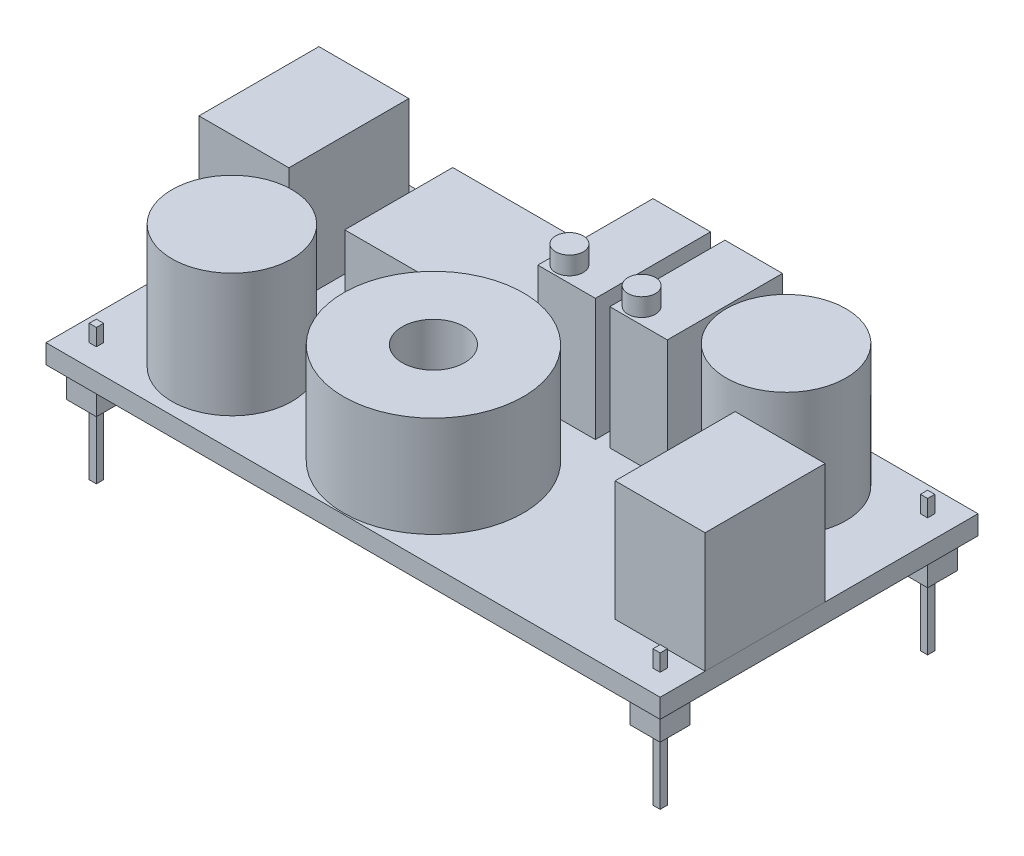
SolidWorks part; units mm, degrees
ref_plane "Plan de face" through (0, 0, 0) normal (0, 0, 1) x (1, 0, 0)
ref_plane "Plan de dessus" through (0, 0, 0) normal (0, 1, 0) x (1, 0, 0)
ref_plane "Plan de droite" through (0, 0, 0) normal (1, 0, 0) x (0, 0, -1)
sketch "Esquisse1" plane through (0, 0, 0) normal (0, 1, 0) x (1, 0, 0)
  line L1 (-25.6, 13.25) -> (25.6, 13.25)
  line L2 (-25.6, 13.25) -> (-25.6, -13.25)
  line L3 (-25.6, -13.25) -> (25.6, -13.25)
  line L4 (25.6, 13.25) -> (25.6, -13.25)
  point P4 (0, 13.25)
  point P6 (-25.6, 0)
  dimension "D1" = 51.2
  dimension "D2" = 26.5
extrude "Boss.-Extru.1" add sketch "Esquisse1" along normal blind 1.6
sketch "Esquisse2" plane through (0, 1.6, 0) normal (0, 1, 0) x (1, 0, 0)
  line L0 (-25.6, 13.25) -> (-25.6, -13.25) construction
  line L1 (-25.6, 9.5) -> (-18.1, 9.5)
  line L2 (-25.6, 9.5) -> (-25.6, -0.5)
  line L3 (-25.6, -0.5) -> (-18.1, -0.5)
  line L4 (-18.1, 9.5) -> (-18.1, -0.5)
  line L5 (25.6, 13.25) -> (-25.6, 13.25) construction
  line L6 (25.6, -13.25) -> (25.6, 13.25) construction
  line L7 (25.6, 0.5) -> (18.1, 0.5)
  line L8 (25.6, 0.5) -> (25.6, -9.5)
  line L9 (25.6, -9.5) -> (18.1, -9.5)
  line L10 (18.1, 0.5) -> (18.1, -9.5)
  line L11 (-25.6, -13.25) -> (25.6, -13.25) construction
  dimension "D1" = 10
  dimension "D2" = 7.5
  dimension "D3" = 3.75
  dimension "D4" = 3.75
extrude "Boss.-Extru.2" add sketch "Esquisse2" along normal blind 10 separate body
sketch "Esquisse3" plane through (0, 1.6, 0) normal (0, 1, 0) x (1, 0, 0)
  line L0 (-25.6, 13.25) -> (-25.6, -13.25) construction
  line L1 (25.6, -13.25) -> (25.6, 13.25) construction
  line L2 (-25.6, -13.25) -> (25.6, -13.25) construction
  line L3 (25.6, 13.25) -> (-25.6, 13.25) construction
  circle A0 centre (15.6, 7.25) radius 5
  circle A1 centre (-16.1, -7.25) radius 5
  dimension "D1" = 10
  dimension "D2" = 9.5
  dimension "D3" = 10
  dimension "D4" = 6
  dimension "D5" = 6
extrude "Boss.-Extru.3" add sketch "Esquisse3" along normal blind 10.3 separate body
sketch "Esquisse4" plane through (0, 1.6, 0) normal (0, 1, 0) x (1, 0, 0)
  line L0 (25.6, 13.25) -> (-25.6, 13.25) construction
  line L1 (-0.5, 12.25) -> (4.3, 12.25)
  line L2 (-0.5, 12.25) -> (-0.5, 2.65)
  line L3 (-0.5, 2.65) -> (4.3, 2.65)
  line L4 (4.3, 12.25) -> (4.3, 2.65)
  line L5 (5.5, 12.25) -> (10.3, 12.25)
  line L6 (5.5, 12.25) -> (5.5, 2.65)
  line L7 (5.5, 2.65) -> (10.3, 2.65)
  line L8 (10.3, 12.25) -> (10.3, 2.65)
  line L9 (25.6, -13.25) -> (25.6, 13.25) construction
  dimension "D1" = 4.8
  dimension "D2" = 9.6
  dimension "D3" = 1.2
  dimension "D4" = 1
  dimension "D5" = 15.3
extrude "Boss.-Extru.4" add sketch "Esquisse4" along normal blind 10.2 separate body
sketch "Esquisse5" plane through (0, 11.8, 0) normal (0, 1, 0) x (1, 0, 0)
  circle A0 centre (0.7843, 4.0049) radius 1.15
  circle A1 centre (6.8045, 4.0049) radius 1.15
  point P4 (0.7843, 4.0049)
  point P5 (6.8045, 4.0049)
  dimension "D1" = 2.3
extrude "Boss.-Extru.5" add sketch "Esquisse5" along normal blind 1.5 separate body
sketch "Esquisse6" plane through (0, 1.6, 0) normal (0, 1, 0) x (1, 0, 0)
  line L0 (-25.6, 13.25) -> (-25.6, -13.25) construction
  line L1 (-25.6, -13.25) -> (25.6, -13.25) construction
  circle A0 centre (-0.9, -5.65) radius 7.5
  circle A1 centre (-0.9, -5.65) radius 2.6
  point P3 (-1.6202, -5.5626)
  dimension "D1" = 15
  dimension "D4" = 5.2
  dimension "D2" = 24.7
  dimension "D3" = 7.6
extrude "Boss.-Extru.6" add sketch "Esquisse6" along normal blind 8.4 separate body
sketch "Esquisse7" plane through (0, 1.6, 0) normal (0, 1, 0) x (1, 0, 0)
  line L0 (25.6, 13.25) -> (-25.6, 13.25) construction
  line L1 (-16.5923, 11.65) -> (-2.5923, 11.65)
  line L2 (-16.5923, 11.65) -> (-16.5923, 2.65)
  line L3 (-16.5923, 2.65) -> (-2.5923, 2.65)
  line L4 (-2.5923, 11.65) -> (-2.5923, 2.65)
  dimension "D1" = 9
  dimension "D2" = 14
  dimension "D3" = 1.6
extrude "Boss.-Extru.7" add sketch "Esquisse7" along normal blind 4.7 separate body contours L2 L1 L4 L3
sketch "Esquisse8" plane through (0, 0, 0) normal (0, -1, 0) x (1, 0, 0)
  line L0 (0, 0) -> (0, 4.7525) construction
  line L1 (-23.8, 11.45) -> (-23.2, 11.45)
  line L2 (-23.8, 11.45) -> (-23.8, 10.85)
  line L3 (-23.8, 10.85) -> (-23.2, 10.85)
  line L4 (-23.2, 11.45) -> (-23.2, 10.85)
  line L5 (0, 0) -> (4.0504, 0) construction
  line L6 (23.2, 11.45) -> (23.2, 10.85)
  line L7 (23.8, 10.85) -> (23.2, 10.85)
  line L8 (23.8, 11.45) -> (23.8, 10.85)
  line L9 (23.8, 11.45) -> (23.2, 11.45)
  line L10 (23.8, -11.45) -> (23.2, -11.45)
  line L11 (23.8, -11.45) -> (23.8, -10.85)
  line L12 (23.8, -10.85) -> (23.2, -10.85)
  line L13 (23.2, -11.45) -> (23.2, -10.85)
  line L14 (-23.2, -11.45) -> (-23.2, -10.85)
  line L15 (-23.8, -10.85) -> (-23.2, -10.85)
  line L16 (-23.8, -11.45) -> (-23.8, -10.85)
  line L17 (-23.8, -11.45) -> (-23.2, -11.45)
  point P7 (-23.6378, 10.9594)
  point P13 (-23.5, 11.45)
  point P14 (23.5, 11.45)
  point P23 (-23.8, 11.15)
  point P24 (-23.8, -11.15)
  dimension "D1" = 0.6
  dimension "D2" = 47
  dimension "D3" = 22.3
extrude "Boss.-Extru.8" add sketch "Esquisse8" along normal blind 8.3 and the other way blind 3 separate body
sketch "Esquisse9" plane through (0, 0, 0) normal (0, -1, 0) x (1, 0, 0)
  line L0 (0, 0) -> (0, 3.5104) construction
  line L1 (-24.75, 12.4) -> (-22.25, 12.4)
  line L2 (-24.75, 12.4) -> (-24.75, 9.9)
  line L3 (-24.75, 9.9) -> (-22.25, 9.9)
  line L4 (-22.25, 12.4) -> (-22.25, 9.9)
  line L5 (0, 0) -> (2.8623, 0) construction
  line L6 (22.25, 12.4) -> (22.25, 9.9)
  line L7 (24.75, 9.9) -> (22.25, 9.9)
  line L8 (24.75, 12.4) -> (24.75, 9.9)
  line L9 (24.75, 12.4) -> (22.25, 12.4)
  line L10 (24.75, -12.4) -> (22.25, -12.4)
  line L11 (24.75, -12.4) -> (24.75, -9.9)
  line L12 (24.75, -9.9) -> (22.25, -9.9)
  line L13 (22.25, -12.4) -> (22.25, -9.9)
  line L14 (-22.25, -12.4) -> (-22.25, -9.9)
  line L15 (-24.75, -9.9) -> (-22.25, -9.9)
  line L16 (-24.75, -12.4) -> (-24.75, -9.9)
  line L17 (-24.75, -12.4) -> (-22.25, -12.4)
  line L18 (-23.2, 11.45) -> (-23.8, 11.45) construction
  line L19 (-23.8, 11.45) -> (-23.8, 10.85) construction
  point P22 (-23.5, 11.45)
  point P23 (-23.5, 12.4)
  point P26 (-23.8, 11.15)
  point P27 (-24.75, 11.15)
  dimension "D1" = 2.5
extrude "Boss.-Extru.9" add sketch "Esquisse9" along normal blind 2.5 separate body
equation "\"D4@Esquisse2\"=\"D3@Esquisse2\""
equation "\"D5@Esquisse3\"=\"D4@Esquisse3\""
